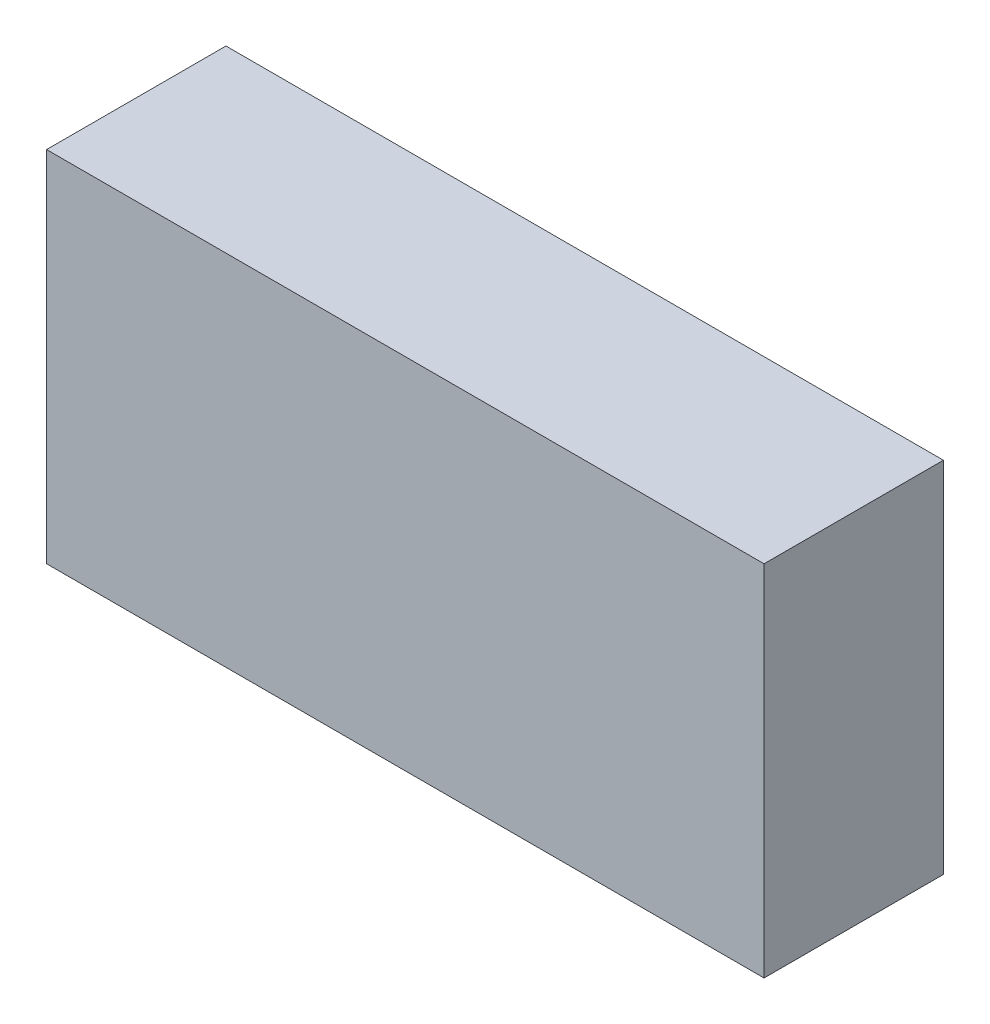
SolidWorks part; units mm, degrees
ref_plane "Front Plane" through (0, 0, 0) normal (0, 0, 1) x (1, 0, 0)
ref_plane "Top Plane" through (0, 0, 0) normal (0, 1, 0) x (1, 0, 0)
ref_plane "Right Plane" through (0, 0, 0) normal (1, 0, 0) x (0, 0, -1)
sketch "Sketch1" plane through (0, 0, 0) normal (0, 0, 1) x (1, 0, 0)
  line L1 (0, 0) -> (40, 0)
  line L2 (0, 0) -> (0, 20)
  line L3 (0, 20) -> (40, 20)
  line L4 (40, 0) -> (40, 20)
extrude "Boss-Extrude1" add sketch "Sketch1" against normal blind 10
